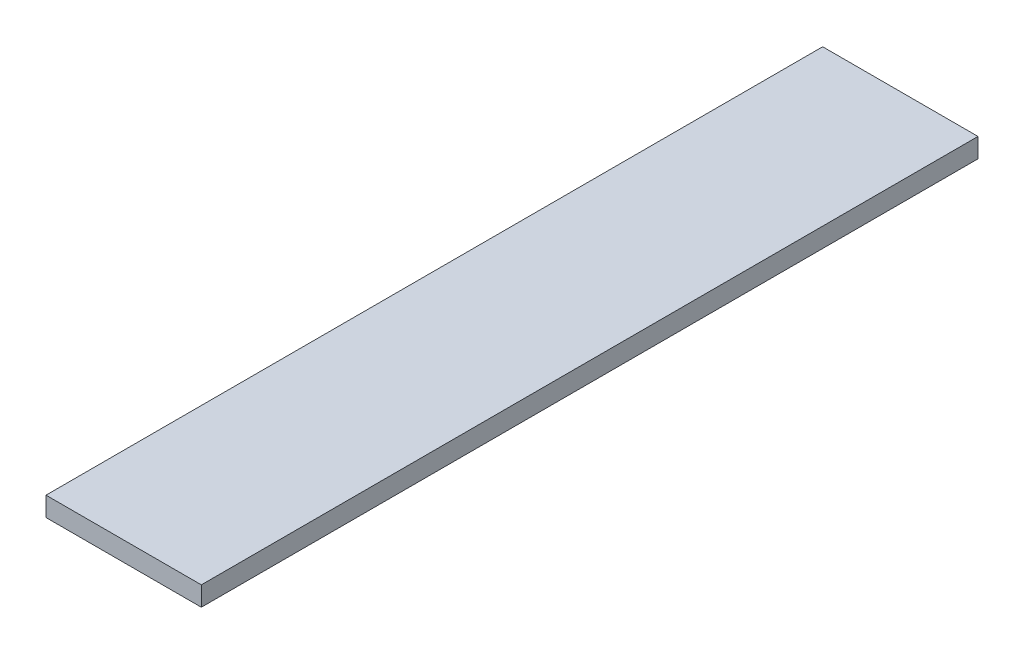
SolidWorks part; units mm, degrees
ref_plane "Front" through (0, 0, 0) normal (0, 0, 1) x (1, 0, 0)
ref_plane "Top" through (0, 0, 0) normal (0, 1, 0) x (1, 0, 0)
ref_plane "Right" through (0, 0, 0) normal (1, 0, 0) x (0, 0, -1)
sketch "Sketch1" plane through (0, 0, 0) normal (0, 1, 0) x (1, 0, 0)
  line L1 (0, 0) -> (25.4, 0)
  line L2 (0, 0) -> (0, 127)
  line L3 (0, 127) -> (25.4, 127)
  line L4 (25.4, 0) -> (25.4, 127)
  dimension "D1" = 25.4
  dimension "D2" = 127
extrude "Boss-Extrude1" add sketch "Sketch1" along normal blind 3.175
